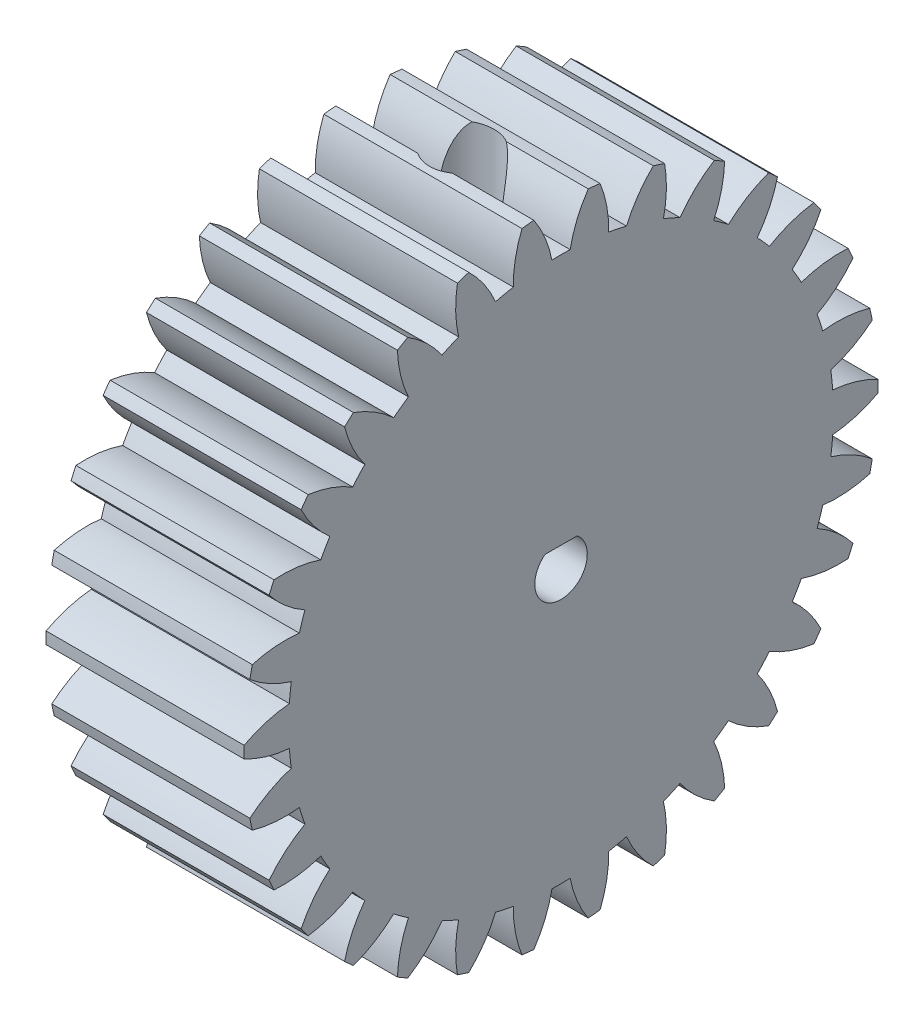
SolidWorks part; units mm, degrees
ref_plane "Plane1" through (0, 0, 0) normal (0, 0, 1) x (1, 0, 0)
ref_plane "Plane2" through (0, 0, 0) normal (0, 1, 0) x (1, 0, 0)
ref_plane "Plane3" through (0, 0, 0) normal (1, 0, 0) x (0, 0, -1)
other "Configuration Table"
sketch "HoldingSke" plane through (0, 0, 0) normal (0, 1, 0) x (1, 0, 0)
  line L0 (0, 0) -> (0.433, -0.25)
  line L1 (-15, 0) -> (100, 0) construction
  line L2 (0, 0) -> (-2.1039, 2.3779)
  line L3 (0, 0) -> (-11.863, 4.5341)
  line L4 (0, 0) -> (7.479, 4.318)
  line L5 (0, 0) -> (-46.8476, -17.4728)
  line L6 (0, 0) -> (-16.5793, -11.1861)
  line L7 (-2.1039, 2.3779) -> (8.6586, 51.2059)
  line L8 (-76.2, 54.61) -> (-76.1, 54.61)
  line L9 (-71.009, 38.7566) -> (-53.1078, 45.2721)
  line L10 (-76.2, 71.12) -> (104.1128, 71.12)
  line L11 (0, 0) -> (-20, 0)
  line L12 (-76.2, 101.6) -> (-76.133, 101.6)
  line L13 (24.9733, 27.94) -> (52.9518, 28.4284)
  line L14 (24.9733, 27.94) -> (24.9743, 27.94)
  line L15 (24.9733, 27.94) -> (100.4006, 29.5858)
  line L16 (-63.627, -2) -> (-12.827, -2)
  circle A0 centre (0, 0) radius 0.4
  circle A1 centre (0, 0) radius 27.499
  circle A2 centre (0, 0) radius 37.5
  circle A3 centre (0, 0) radius 0.4
  dimension "MHD" = 54.998
  dimension "Hub_dia" = 75
  dimension "Bore" = 0.8
  dimension "MBD" = 0.8
  dimension "Num_teeth" = 30
  dimension "Pitch" = 0.5
  dimension "Overall_len" = 50
  dimension "Show_teeth" = 30
  dimension "Thickness" = 20
  dimension "OAL" = 50.0001
  dimension "T_dim" = 0.1
  dimension "Ap" = 20
  dimension "H" = 19.05
  dimension "Pitch_radius" = 180.3128
  dimension "Width" = 20
  dimension "Backlash" = 0.067
  dimension "Addendum_fac" = 1
  dimension "Dedendum_fac" = 1.25
  dimension "Clearance_fac" = 0.25
  dimension "Dedendum_add" = 0.001
  dimension "Module" = 2
sketch "BasProSke" plane through (0, 0, 0) normal (0, 1, 0) x (1, 0, 0)
  line L0 (-10, 0) -> (60, 0) construction
  line L1 (0, 0) -> (0, 32)
  line L2 (0, 0) -> (20, 0)
  line L3 (20, 0) -> (20, 32)
  line L4 (20, 32) -> (0, 32)
  dimension "Thickness" = 20
  dimension "Diameter" = 64
revolve "Base-Revolve" add sketch "BasProSke" angle 360 about L0
sketch "TooCutSke" plane through (0, 0, 0) normal (1, 0, 0) x (0, 0, -1)
  line L1 (0, 0) -> (0, 107) construction
  line L2 (0, 0) -> (-1.6873, 29.9525) construction
  line L3 (0, 0) -> (-6.2643, 59.6013) construction
  line L4 (-1.6873, 29.9525) -> (-3.1322, 29.8007) construction
  arc A0 (0.9186, 27.4837) -> (-0.9186, 27.4837) centre (0, 0) ccw
  arc A1 (2.7618, 31.9061) -> (-2.7618, 31.9061) centre (0, 0) ccw
  circle A2 centre (0, 0) radius 30 construction
  circle A3 centre (0, 0) radius 28.1908 construction
  arc A4 (-0.9186, 27.4837) -> (-2.7618, 31.9061) centre (-12.6936, 25.1712) ccw
  arc A5 (2.7618, 31.9061) -> (0.9186, 27.4837) centre (12.6936, 25.1712) ccw
  dimension "Root_dia" = 54.998
  dimension "Overcut_dia" = 64.0508
  dimension "Pitch_dia" = 60
  dimension "Base_dia" = 56.3816
  dimension "Flank_rad" = 12
  dimension "Half_ang" = 6
  dimension "Half_CT" = 1.4528
extrude "ToothCut" cut sketch "TooCutSke" along normal through all
fillet "Breaks" [suppressed] radius 0.04
fillet "RootFillets" [suppressed] radius 0.501
pattern_circular "TeethCuts" count 30 every 12 about axis through (-10, 0, 0) along (1, 0, 0) of "ToothCut", "RootFillets", "Breaks"
sketch "HubNeaOneSke" plane through (0, 0, 0) normal (-1, 0, 0) x (0, 0, 1)
  circle A0 centre (0, 0) radius 27.499
  dimension "Diameter" = 54.998
extrude "HubNearOne" [suppressed] add sketch "HubNeaOneSke" along normal blind 30.0001
sketch "HubNeaBotSke" plane through (0, 0, 0) normal (-1, 0, 0) x (0, 0, 1)
  circle A0 centre (0, 0) radius 27.499
  dimension "Diameter" = 54.998
extrude "HubNearBoth" [suppressed] add sketch "HubNeaBotSke" along normal blind 15
ref_plane "FarPln" through (20, 0, 0) normal (1, 0, 0) x (0, 0, -1)
sketch "HubFarSke" plane through (20, 0, 0) normal (1, 0, 0) x (0, 0, -1)
  circle A0 centre (0, 0) radius 27.499
  dimension "Diameter" = 54.998
extrude "HubFar" [suppressed] add sketch "HubFarSke" along normal blind 15
sketch "BorSke" plane through (0, 0, 0) normal (1, 0, 0) x (0, 0, -1)
  circle A0 centre (0, 0) radius 0.4
  dimension "Diameter" = 0.8
extrude "Bore" cut sketch "BorSke" along normal mid plane 100.0001
sketch "KeySke" plane through (0, 0, 0) normal (1, 0, 0) x (0, 0, -1)
  line L0 (-0.05, 0) -> (-0.05, 0.5)
  line L1 (-0.05, 0.5) -> (0.05, 0.5)
  line L2 (0.05, 0.5) -> (0.05, 0)
  line L3 (0, 0) -> (0, 34) construction
  line L4 (-0.05, 0) -> (0.05, 0)
  dimension "Offset" = 0.5
  dimension "Width" = 0.1
extrude "Keyway" [suppressed] cut sketch "KeySke" along normal mid plane 100.0001
pattern_circular "Keyway2" [suppressed] count 2 every 90 about axis through (-10, 0, 0) along (1, 0, 0)
sketch "Sketch1" plane through (0, 0, 0) normal (-1, 0, 0) x (0, 0, 1)
  line L0 (-1.6163, 2.1) -> (1.6163, 2.1)
  arc A0 (-1.6163, 2.1) -> (1.6163, 2.1) centre (0, 0) ccw
  dimension "D1" = 5.3
  dimension "D2" = 2.1
extrude "Cut-Extrude1" cut sketch "Sketch1" against normal through all
ref_plane "Plane4" through (0, 10, 0) normal (0, 1, 0) x (1, 0, 0)
sketch "Sketch2" plane through (0, 10, 0) normal (0, 1, 0) x (1, 0, 0)
  line L0 (0, 0) -> (20, 0) construction
  line L1 (20, -1.6163) -> (20, 1.6163) construction
  circle A0 centre (10, 0) radius 3.25
  dimension "D1" = 6.5
extrude "Cut-Extrude2" cut sketch "Sketch2" along normal through all
sketch "Sketch3" plane through (0, 10, 0) normal (0, 1, 0) x (1, 0, 0)
  circle A0 centre (10, 0) radius 1.4
  dimension "D1" = 2.8
extrude "Cut-Extrude3" cut sketch "Sketch3" against normal up to next
equation "' \"Module@HoldingSke\" = 6.35"
equation "' \"Num_teeth@HoldingSke\" = 12"
equation "' \"Ap@HoldingSke\" =  20"
equation "' \"Ap@HoldingSke\" = 20"
equation "' \"Width@HoldingSke\" = 0.5 * 25.4"
equation "' \"Hub_dia@HoldingSke\"= 1 * 25.4"
equation "' \"Hub_dia@HoldingSke\" = 1 * 25.4"
equation "' \"Overall_len@HoldingSke\" = 1.0 * 25.4"
equation "' \"Bore@HoldingSke\" = 0.75 * 25.4"
equation "' \"T_dim@HoldingSke\" = 0.1 * 25.4"
equation "' \"Width@KeySke\" = 0.25 * 25.4"
equation "' \"Show_teeth@HoldingSke\" = 13"
equation "' \"Backlash@HoldingSke\" = 0.009 * 25.4"
equation "' \"Addendum_fac@HoldingSke\" = 1.0"
equation "' \"Dedendum_fac@HoldingSke\" = 1.25"
equation "' \"Dedendum_add@HoldingSke\" = 0.00005 * 25.4"
equation "' \"Clearance_fac@HoldingSke\" = 0.25"
equation "\"Pitch@HoldingSke\" = 1 / \"Module@HoldingSke\""
equation "\"Overcut_dia@TooCutSke\" = (\"Num_teeth@HoldingSke\" + 2 * \"Addendum_fac@HoldingSke\") / \"Pitch@HoldingSke\" + 0.002 * 25.4"
equation "\"Pitch_dia@TooCutSke\" = \"Num_teeth@HoldingSke\" / \"Pitch@HoldingSke\""
equation "\"Base_dia@TooCutSke\" = \"Num_teeth@HoldingSke\" / \"Pitch@HoldingSke\" * cos((\"Ap@HoldingSke\"  * 3.14159265 / 180))"
equation "\"Root_dia@TooCutSke\" = (\"Num_teeth@HoldingSke\" + 2) / \"Pitch@HoldingSke\" - 2 * (\"Addendum_fac@HoldingSke\" + \"Dedendum_fac@HoldingSke\") / \"Pitch@HoldingSke\" - \"Dedendum_add@HoldingSke\" * 2"
equation "\"Half_ang@TooCutSke\" = 180 / \"Num_teeth@HoldingSke\""
equation "\"Half_CT@TooCutSke\" = \"Num_teeth@HoldingSke\" / \"Pitch@HoldingSke\" * sin((3.14159265 / 2 / \"Num_teeth@HoldingSke\")) / 2 - 7 * \"Backlash@HoldingSke\" / 4"
equation "\"Flank_rad@TooCutSke\" = \"Num_teeth@HoldingSke\" / \"Pitch@HoldingSke\" / 5"
equation "\"Radius@RootFillets\" = \"Clearance_fac@HoldingSke\" / \"Pitch@HoldingSke\" + \"Dedendum_add@HoldingSke\""
equation "\"Break_rad@Breaks\" = 0.02 / \"Pitch@HoldingSke\""
equation "\"Thickness@HoldingSke\" = \"Width@HoldingSke\""
equation "\"OAL@HoldingSke\" = \"Thickness@HoldingSke\""
equation "\"MHD@HoldingSke\" = (\"Num_teeth@HoldingSke\" + 2) / \"Pitch@HoldingSke\" - 2 * (\"Addendum_fac@HoldingSke\" + \"Dedendum_fac@HoldingSke\")  / \"Pitch@HoldingSke\" - \"Dedendum_add@HoldingSke\" * 2"
equation "\"MBD@HoldingSke\" = (\"Num_teeth@HoldingSke\" + 2) / \"Pitch@HoldingSke\" - 2 * (\"Addendum_fac@HoldingSke\" + \"Dedendum_fac@HoldingSke\")  / \"Pitch@HoldingSke\" - \"Dedendum_add@HoldingSke\" * 2 - 0.002 * 25.4"
equation "\"MHD@HoldingSke\" = ((sgn( \"MHD@HoldingSke\" - \"Hub_dia@HoldingSke\" )-1)*( \"MHD@HoldingSke\" - \"Hub_dia@HoldingSke\" ))/-2+ \"Hub_dia@HoldingSke\""
equation "\"MBD@HoldingSke\" = ((sgn( \"MBD@HoldingSke\" - \"Bore@HoldingSke\" )-1)*( \"MBD@HoldingSke\" - \"Bore@HoldingSke\" ))/-2+ \"Bore@HoldingSke\""
equation "\"OAL@HoldingSke\" = ((sgn( \"OAL@HoldingSke\" - \"Overall_len@HoldingSke\" )+1)*( \"OAL@HoldingSke\" - \"Overall_len@HoldingSke\" ))/2 + \"Overall_len@HoldingSke\" + 0.000002 * 25.4"
equation "\"Num_teeth@TeethCuts\" = int( \"Show_teeth@HoldingSke\" ) + 1"
equation "\"Num_teeth@TeethCuts\" = ((sgn( \"Num_teeth@TeethCuts\" - \"Num_teeth@HoldingSke\" )-1)*( \"Num_teeth@TeethCuts\" - \"Num_teeth@HoldingSke\" ))/-2+ \"Num_teeth@HoldingSke\""
equation "\"Num_teeth@TeethCuts\" = ((sgn( \"Num_teeth@TeethCuts\" - 2.0)+1)*( \"Num_teeth@TeethCuts\" - 2.0))/2 +2.0"
equation "\"Angle@TeethCuts\" = 360.0 / \"Num_teeth@HoldingSke\""
equation "\"Diameter@BasProSke\" = (\"Num_teeth@HoldingSke\" + 2 * \"Addendum_fac@HoldingSke\") / \"Pitch@HoldingSke\""
equation "\"Thickness@BasProSke\"  = \"Thickness@HoldingSke\""
equation "' \"Fillet_rad@BasProSke\" =  \"Thickness@HoldingSke\" * 0.05"
equation "' \"Fillet_rad@BasProSke\" = \"Thickness@HoldingSke\" * 0.05"
equation "\"MHD@HoldingSke\" = ((sgn( \"MHD@HoldingSke\" - \"Root_dia@TooCutSke\" )-1)*( \"MHD@HoldingSke\" - \"Root_dia@TooCutSke\" ))/-2+ \"Root_dia@TooCutSke\""
equation "\"Diameter@HubNeaOneSke\" = \"MHD@HoldingSke\""
equation "\"Length@HubNearOne\" = \"OAL@HoldingSke\" - \"Thickness@BasProSke\""
equation "\"Diameter@HubNeaBotSke\" = \"MHD@HoldingSke\""
equation "\"Length@HubNearBoth\" = ( \"OAL@HoldingSke\" - \"Thickness@BasProSke\" ) / 2.0"
equation "\"Thickness@FarPln\" = \"Thickness@BasProSke\""
equation "\"Diameter@HubFarSke\" = \"MHD@HoldingSke\""
equation "\"Length@HubFar\" = ( \"OAL@HoldingSke\" - \"Thickness@BasProSke\" ) / 2.0"
equation "\"Diameter@BorSke\" = \"MBD@HoldingSke\""
equation "\"D1@Bore\" = \"OAL@HoldingSke\" * 2.0"
equation "\"D1@Keyway\" = \"OAL@HoldingSke\" * 2.0"
equation "\"Offset@KeySke\" = \"T_dim@HoldingSke\" + \"MBD@HoldingSke\" / 2.0"
